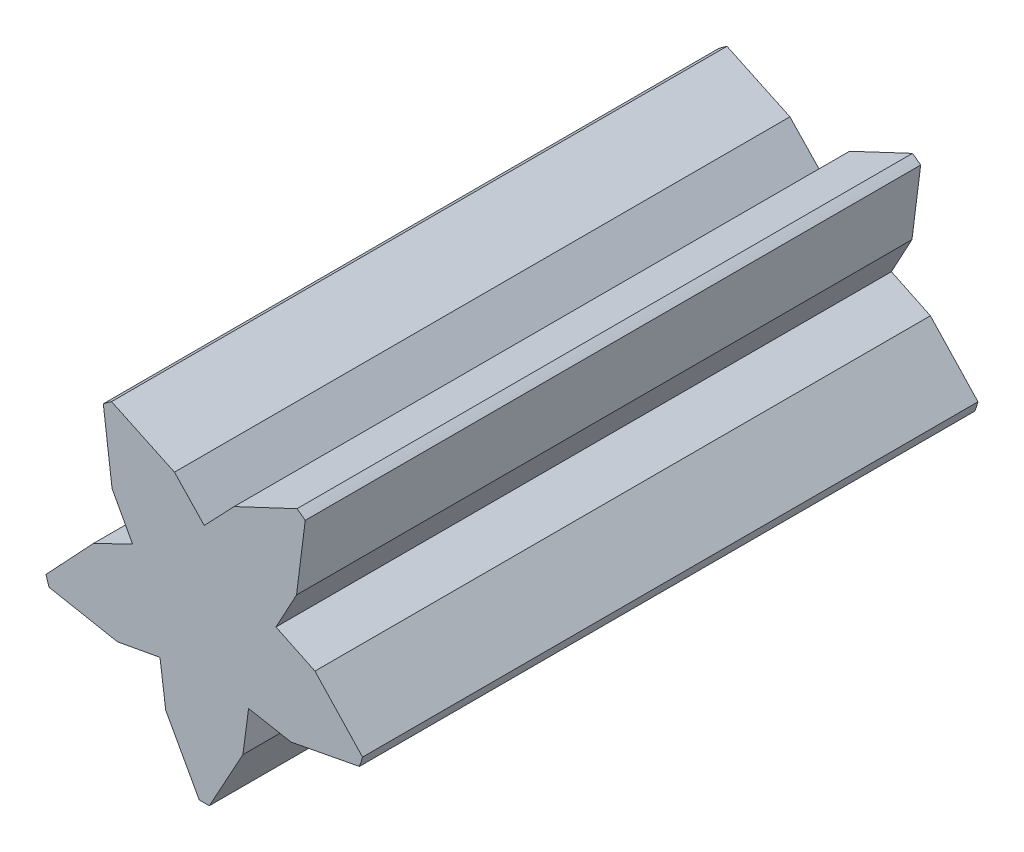
SolidWorks part; units mm, degrees
ref_plane "Front Plane" through (0, 0, 0) normal (0, 0, 1) x (1, 0, 0)
ref_plane "Top Plane" through (0, 0, 0) normal (0, 1, 0) x (1, 0, 0)
ref_plane "Right Plane" through (0, 0, 0) normal (1, 0, 0) x (0, 0, -1)
sketch "Sketch1" plane through (0, 0, 0) normal (0, 0, 1) x (1, 0, 0)
  line L1 (1.7678, -1.7678) -> (-1.7678, -1.7678) construction
  line L2 (1.7678, -1.7678) -> (1.7678, 1.7678) construction
  line L3 (1.7678, 1.7678) -> (-1.7678, 1.7678) construction
  line L4 (-1.7678, -1.7678) -> (-1.7678, 1.7678) construction
  line L5 (1.7678, -1.7678) -> (-1.7678, 1.7678) construction
  line L6 (1.7678, 1.7678) -> (-1.7678, -1.7678) construction
  circle A0 centre (0, 0) radius 7.5
  circle A1 centre (0, 0) radius 2.5 construction
  dimension "D1" = 15
  dimension "D2" = 5
extrude "Boss-Extrude1" add sketch "Sketch1" along normal blind 28
sketch "Sketch2" plane through (0, 0, 0) normal (0, 0, 1) x (1, 0, 0)
  line L0 (0, 0) -> (0, 10.088) construction
  line L1 (0, 3.4293) -> (-1.3565, 4.8529)
  line L2 (-1.3565, 4.8529) -> (-4.2191, 6.2007)
  line L3 (-4.2191, 6.2007) -> (0, 11.2516)
  line L4 (4.2191, 6.2007) -> (0, 11.2516)
  line L5 (1.3565, 4.8529) -> (4.2191, 6.2007)
  line L6 (0, 3.4293) -> (1.3565, 4.8529)
  circle A14 centre (0, 0) radius 7.5 construction
  point P16 (0, 7.5)
extrude "Cut-Extrude1" cut sketch "Sketch2" along normal through all
pattern_circular "CirPattern1" count 5 over 360 about axis through (0, 0, 0) along (0, 0, 1) of "Cut-Extrude1"
sketch "Sketch3" plane through (0, 0, 0) normal (0, 0, 1) x (1, 0, 0)
  circle A0 centre (0, 0) radius 7.5
  dimension "D1" = 15
